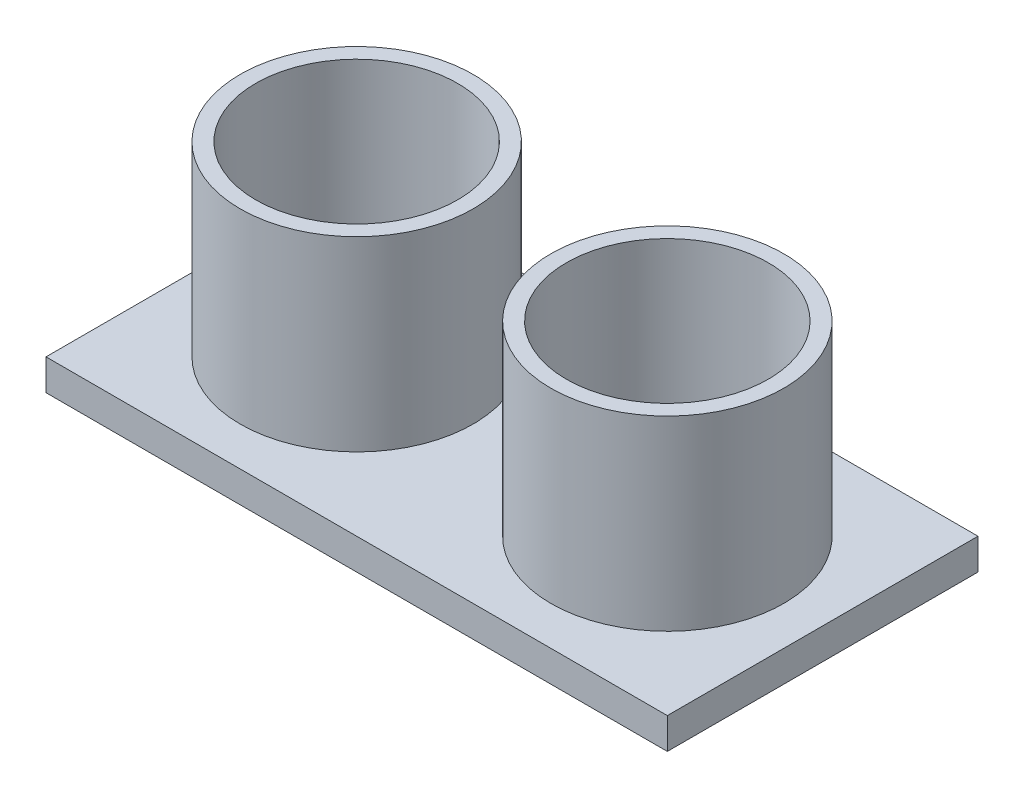
SolidWorks part; units mm, degrees
ref_plane "Front Plane" through (0, 0, 0) normal (0, 0, 1) x (1, 0, 0)
ref_plane "Top Plane" through (0, 0, 0) normal (0, 1, 0) x (1, 0, 0)
ref_plane "Right Plane" through (0, 0, 0) normal (1, 0, 0) x (0, 0, -1)
sketch "Sketch1" plane through (0, 0, 0) normal (0, 1, 0) x (1, 0, 0)
  line L1 (-20, 10) -> (20, 10)
  line L2 (-20, 10) -> (-20, -10)
  line L3 (-20, -10) -> (20, -10)
  line L4 (20, 10) -> (20, -10)
  line L5 (-20, 10) -> (20, -10) construction
  line L6 (-20, -10) -> (20, 10) construction
  point P0 (0, 0)
  dimension "D1" = 40
  dimension "D2" = 20
extrude "Boss-Extrude1" add sketch "Sketch1" along normal blind 2
sketch "Sketch2" plane through (0, 2, 0) normal (0, 1, 0) x (1, 0, 0)
  line L0 (21.5499, 0) -> (-22.9865, 0) construction
  line L2 (-20, 10) -> (-20, -10) construction
  line L3 (20, -10) -> (20, 10) construction
  circle A0 centre (-10, 0) radius 7.5
  circle A1 centre (10, 0) radius 7.5
  dimension "D1" = 15
  dimension "15" = 15
  dimension "D2" = 10
  dimension "D3" = 10
extrude "Boss-Extrude2" add sketch "Sketch2" along normal blind 12
sketch "Sketch3" plane through (0, 14, 0) normal (0, 1, 0) x (1, 0, 0)
  circle A0 centre (-10, 0) radius 6.5
  dimension "D1" = 13
extrude "Cut-Extrude1" cut sketch "Sketch3" against normal blind 12
sketch "Sketch7" plane through (0, 14, 0) normal (0, 1, 0) x (1, 0, 0)
  circle A0 centre (10, 0) radius 6.5
  dimension "D1" = 13
extrude "Cut-Extrude2" cut sketch "Sketch7" against normal blind 12
sketch "Sketch9" plane through (0, 2, 0) normal (0, 1, 0) x (1, 0, 0)
  line L0 (-3, 9) -> (3, 9)
  line L1 (-3, 6) -> (3, 6)
  line L2 (20, 10) -> (-20, 10) construction
  line L3 (-20, 10) -> (-20, -10) construction
  line L4 (20, -10) -> (20, 10) construction
  arc A0 (3, 9) -> (3, 6) centre (3, 7.5) cw
  arc A1 (-3, 9) -> (-3, 6) centre (-3, 7.5) ccw
  dimension "D3" = 1.5
  dimension "D1" = 1
  dimension "D2" = 3
  dimension "D4" = 17
  dimension "D5" = 17
extrude "Boss-Extrude3" add sketch "Sketch9" along normal blind 2
